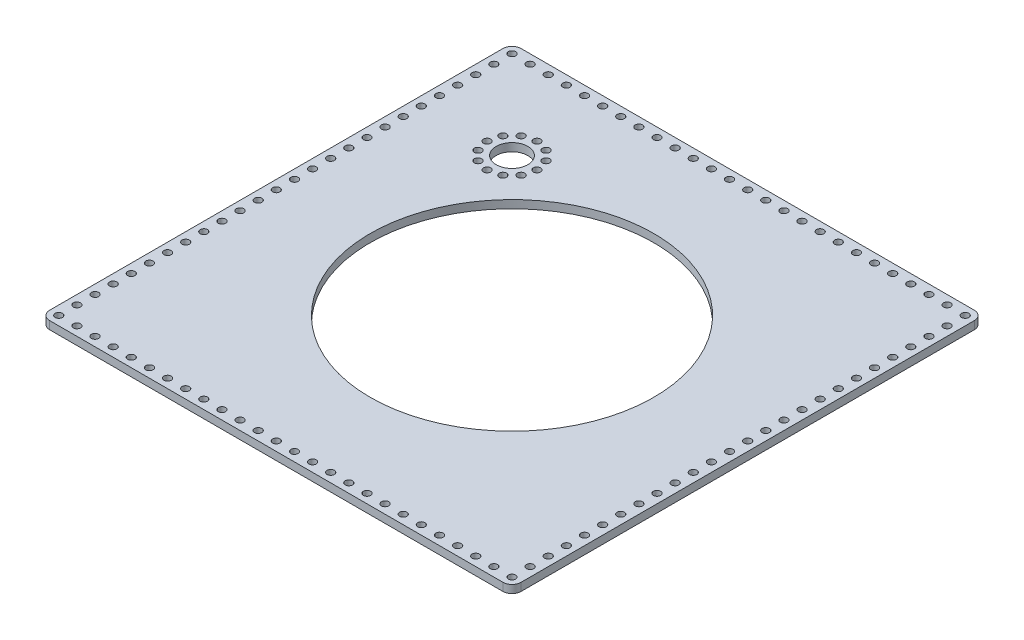
SolidWorks part; units mm, degrees
material "ABS PC"
ref_plane "Front Plane" through (0, 0, 0) normal (0, 0, 1) x (1, 0, 0)
ref_plane "Top Plane" through (0, 0, 0) normal (0, 1, 0) x (1, 0, 0)
ref_plane "Right Plane" through (0, 0, 0) normal (1, 0, 0) x (0, 0, -1)
ref_plane "Plane1" through (0, 0, 0) normal (0, -1, 0) x (1, 0, 0)
sketch "Sketch1" plane through (0, 0, 0) normal (0, -1, 0) x (1, 0, 0)
  line L8 (-165.1, 158.75) -> (-165.1, -158.75)
  line L9 (-158.75, -165.1) -> (158.75, -165.1)
  line L10 (165.1, -158.75) -> (165.1, 158.75)
  line L11 (158.75, 165.1) -> (-158.75, 165.1)
  line L12 (165.1, 0) -> (0, 0) construction
  line L13 (0, 0) -> (0, 165.1) construction
  line L14 (-158.75, 158.75) -> (-146.05, 158.75) construction
  line L15 (-158.75, 158.75) -> (-158.75, 146.05) construction
  line L16 (-158.75, -158.75) -> (-146.05, -158.75) construction
  line L17 (-96.9868, 96.9868) -> (-96.9868, -96.9868) construction
  line L18 (-96.9868, -96.9868) -> (96.9868, -96.9868) construction
  line L19 (96.9868, -96.9868) -> (96.9868, 96.9868) construction
  line L20 (96.9868, 96.9868) -> (-96.9868, 96.9868) construction
  line L21 (0, 0) -> (-96.9868, 0) construction
  line L22 (0, -96.9868) -> (0, 0) construction
  circle A16 centre (0, 0) radius 99.375
  circle A17 centre (-158.75, -158.75) radius 2.5527
  circle A18 centre (-146.05, 158.75) radius 2.5527
  circle A19 centre (-133.35, 158.75) radius 2.5527
  circle A20 centre (-120.65, 158.75) radius 2.5527
  circle A21 centre (-107.95, 158.75) radius 2.5527
  circle A22 centre (-95.25, 158.75) radius 2.5527
  circle A23 centre (-82.55, 158.75) radius 2.5527
  circle A24 centre (-69.85, 158.75) radius 2.5527
  circle A25 centre (-57.15, 158.75) radius 2.5527
  circle A26 centre (-44.45, 158.75) radius 2.5527
  circle A27 centre (-31.75, 158.75) radius 2.5527
  circle A28 centre (-19.05, 158.75) radius 2.5527
  circle A29 centre (-6.35, 158.75) radius 2.5527
  circle A30 centre (6.35, 158.75) radius 2.5527
  circle A31 centre (19.05, 158.75) radius 2.5527
  circle A32 centre (31.75, 158.75) radius 2.5527
  circle A33 centre (44.45, 158.75) radius 2.5527
  circle A34 centre (57.15, 158.75) radius 2.5527
  circle A35 centre (69.85, 158.75) radius 2.5527
  circle A36 centre (82.55, 158.75) radius 2.5527
  circle A37 centre (95.25, 158.75) radius 2.5527
  circle A38 centre (107.95, 158.75) radius 2.5527
  circle A39 centre (120.65, 158.75) radius 2.5527
  circle A41 centre (-158.75, 158.75) radius 2.5527
  circle A42 centre (133.35, 158.75) radius 2.5527
  circle A43 centre (146.05, 158.75) radius 2.5527
  circle A45 centre (-158.75, 146.05) radius 2.5527
  circle A46 centre (158.75, 146.05) radius 2.5527
  circle A47 centre (-158.75, 133.35) radius 2.5527
  circle A48 centre (158.75, 133.35) radius 2.5527
  circle A49 centre (-158.75, 120.65) radius 2.5527
  circle A50 centre (158.75, 120.65) radius 2.5527
  circle A51 centre (-158.75, 107.95) radius 2.5527
  circle A52 centre (158.75, 107.95) radius 2.5527
  circle A53 centre (-158.75, 95.25) radius 2.5527
  circle A54 centre (158.75, 95.25) radius 2.5527
  circle A55 centre (-158.75, 82.55) radius 2.5527
  circle A56 centre (158.75, 82.55) radius 2.5527
  circle A57 centre (-158.75, 69.85) radius 2.5527
  circle A58 centre (158.75, 69.85) radius 2.5527
  circle A59 centre (-158.75, 57.15) radius 2.5527
  circle A60 centre (158.75, 57.15) radius 2.5527
  circle A61 centre (-158.75, 44.45) radius 2.5527
  circle A62 centre (158.75, 44.45) radius 2.5527
  circle A63 centre (-158.75, 31.75) radius 2.5527
  circle A64 centre (158.75, 158.75) radius 2.5527
  circle A65 centre (158.75, 31.75) radius 2.5527
  circle A66 centre (-158.75, 19.05) radius 2.5527
  circle A67 centre (158.75, 19.05) radius 2.5527
  circle A68 centre (-158.75, 6.35) radius 2.5527
  circle A69 centre (158.75, 6.35) radius 2.5527
  circle A70 centre (-158.75, -6.35) radius 2.5527
  circle A71 centre (158.75, -6.35) radius 2.5527
  circle A72 centre (-158.75, -19.05) radius 2.5527
  circle A73 centre (158.75, -19.05) radius 2.5527
  circle A74 centre (-158.75, -31.75) radius 2.5527
  circle A75 centre (158.75, -31.75) radius 2.5527
  circle A76 centre (-158.75, -44.45) radius 2.5527
  circle A77 centre (158.75, -44.45) radius 2.5527
  circle A78 centre (-158.75, -57.15) radius 2.5527
  circle A79 centre (158.75, -57.15) radius 2.5527
  circle A80 centre (-158.75, -69.85) radius 2.5527
  circle A81 centre (158.75, -69.85) radius 2.5527
  circle A82 centre (-158.75, -82.55) radius 2.5527
  circle A83 centre (158.75, -82.55) radius 2.5527
  circle A84 centre (-158.75, -95.25) radius 2.5527
  circle A85 centre (158.75, -95.25) radius 2.5527
  circle A86 centre (-158.75, -107.95) radius 2.5527
  circle A87 centre (158.75, -107.95) radius 2.5527
  circle A88 centre (-158.75, -120.65) radius 2.5527
  circle A89 centre (158.75, -120.65) radius 2.5527
  circle A90 centre (-158.75, -133.35) radius 2.5527
  circle A91 centre (158.75, -133.35) radius 2.5527
  circle A92 centre (-158.75, -146.05) radius 2.5527
  circle A93 centre (158.75, -146.05) radius 2.5527
  circle A96 centre (-146.05, -158.75) radius 2.5527
  circle A97 centre (-133.35, -158.75) radius 2.5527
  circle A98 centre (-120.65, -158.75) radius 2.5527
  circle A99 centre (-107.95, -158.75) radius 2.5527
  circle A100 centre (-95.25, -158.75) radius 2.5527
  circle A101 centre (-82.55, -158.75) radius 2.5527
  circle A102 centre (-69.85, -158.75) radius 2.5527
  circle A103 centre (-57.15, -158.75) radius 2.5527
  circle A104 centre (-44.45, -158.75) radius 2.5527
  circle A105 centre (-31.75, -158.75) radius 2.5527
  circle A106 centre (-19.05, -158.75) radius 2.5527
  circle A107 centre (-6.35, -158.75) radius 2.5527
  circle A108 centre (6.35, -158.75) radius 2.5527
  circle A130 centre (-96.9868, -79.5243) radius 2.5527
  arc A132 (-165.1, -158.75) -> (-158.75, -165.1) centre (-158.75, -158.75) ccw
  arc A133 (158.75, -165.1) -> (165.1, -158.75) centre (158.75, -158.75) ccw
  arc A134 (165.1, 158.75) -> (158.75, 165.1) centre (158.75, 158.75) ccw
  arc A135 (-158.75, 165.1) -> (-165.1, 158.75) centre (-158.75, 158.75) ccw
  circle A136 centre (19.05, -158.75) radius 2.5527
  circle A137 centre (31.75, -158.75) radius 2.5527
  circle A138 centre (44.45, -158.75) radius 2.5527
  circle A139 centre (57.15, -158.75) radius 2.5527
  circle A140 centre (69.85, -158.75) radius 2.5527
  circle A141 centre (82.55, -158.75) radius 2.5527
  circle A142 centre (95.25, -158.75) radius 2.5527
  circle A143 centre (107.95, -158.75) radius 2.5527
  circle A144 centre (120.65, -158.75) radius 2.5527
  circle A145 centre (133.35, -158.75) radius 2.5527
  circle A146 centre (146.05, -158.75) radius 2.5527
  circle A147 centre (158.75, -158.75) radius 2.5527
  circle A148 centre (-96.9868, -96.9868) radius 11.1125
  circle A149 centre (-96.9868, -96.9868) radius 17.4625 construction
  circle A150 centre (-88.2555, -81.8638) radius 2.5527
  circle A151 centre (-81.8638, -88.2555) radius 2.5527
  circle A152 centre (-79.5243, -96.9868) radius 2.5527
  circle A153 centre (-81.8638, -105.718) radius 2.5527
  circle A154 centre (-88.2555, -112.1097) radius 2.5527
  circle A155 centre (-96.9868, -114.4493) radius 2.5527
  circle A156 centre (-105.718, -112.1097) radius 2.5527
  circle A157 centre (-112.1097, -105.718) radius 2.5527
  circle A158 centre (-114.4493, -96.9868) radius 2.5527
  circle A159 centre (-112.1097, -88.2555) radius 2.5527
  circle A160 centre (-105.718, -81.8638) radius 2.5527
  circle A161 centre (0, 0) radius 127 construction
  circle A162 centre (-96.9868, -96.9868) radius 10.16 construction
  circle A163 centre (-158.75, -158.75) radius 2.5527 [skipped]
  circle A164 centre (158.75, -158.75) radius 2.5527 [skipped]
  circle A165 centre (158.75, 158.75) radius 2.5527 [skipped]
  point P27 (-96.9868, -96.9868)
  point P28 (0, 0)
  dimension "D1" = 198.75
  dimension "D2" = 6.35
  dimension "D6" = 5.1054
  dimension "D11" = 22.225
  dimension "D12" = 34.925
  dimension "D13" = 254
  dimension "D15" = 20.32
  dimension "D3" = 165.1
  dimension "D5" = 12.7
  dimension "D8" = 12.7
  dimension "D10" = 12.7
  dimension "D14" = 12
  dimension "D4" = 26
  dimension "D7" = 26
  dimension "D9" = 26
extrude "Boss-Extrude1" add sketch "Sketch1" against normal blind 5.588
